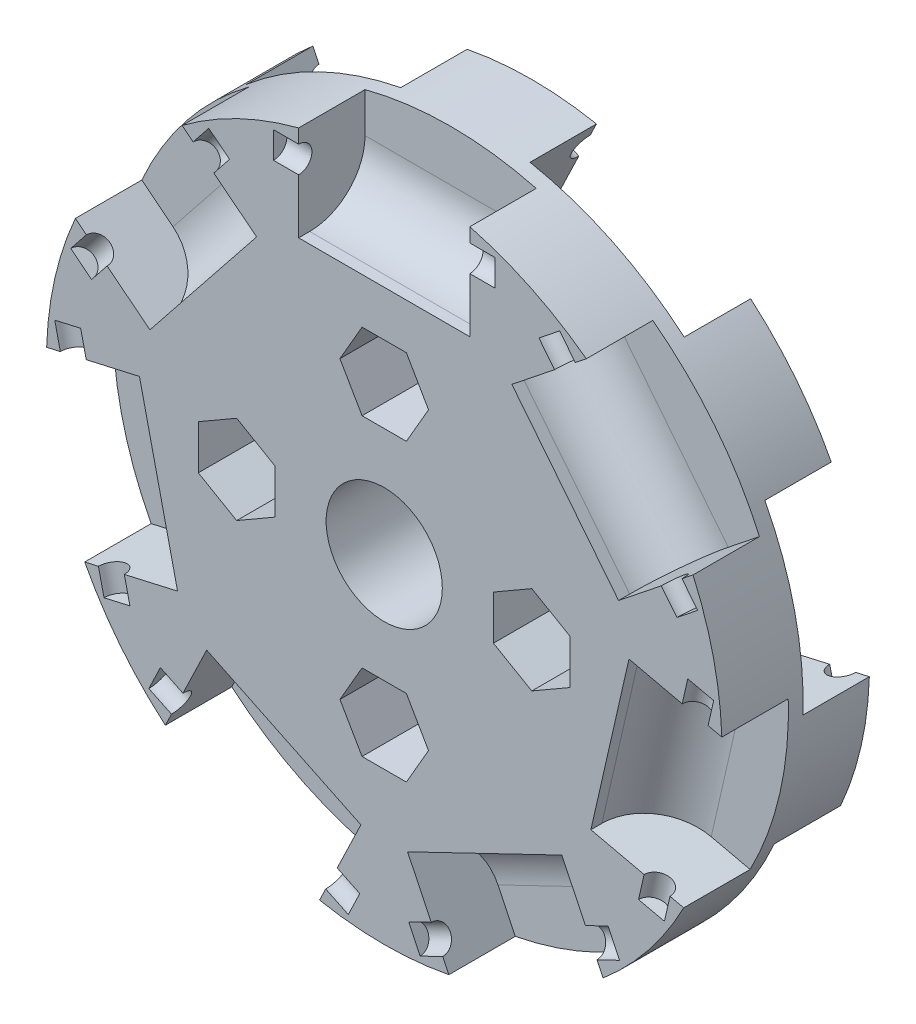
SolidWorks part; units mm, degrees
other "Markup1"
sketch "Sketch8" plane through (32.7336, 32.7336, 0) normal (0.5701, 0.1846, 0.8006) x (0.8043, 0.0736, -0.5897)
ref_plane "Front Plane" through (0, 0, 0) normal (0, 0, 1) x (1, 0, 0)
ref_plane "Top Plane" through (0, 0, 0) normal (0, 1, 0) x (1, 0, 0)
ref_plane "Right Plane" through (0, 0, 0) normal (1, 0, 0) x (0, 0, -1)
sketch "Sketch1" plane through (0, 0, 0) normal (0, 0, 1) x (1, 0, 0)
  circle A0 centre (0, 0) radius 29.0703
  dimension "D1" = 58.1406
extrude "Boss-Extrude2" add sketch "Sketch1" against normal blind 6.35
sketch "Sketch2" plane through (0, 0, 0) normal (0, 0, 1) x (1, 0, 0)
  line L1 (-12.7, 29.0703) -> (12.7, 29.0703) construction
  line L2 (-7.366, 30.3403) -> (7.366, 30.3403)
  line L3 (-7.366, 30.3403) -> (-7.366, 19.9263)
  line L4 (-7.366, 19.9263) -> (7.366, 19.9263)
  line L5 (7.366, 30.3403) -> (7.366, 19.9263)
  line L6 (-7.366, 30.3403) -> (7.366, 19.9263) construction
  line L7 (-7.366, 19.9263) -> (7.366, 30.3403) construction
  line L35 (0, 0) -> (0, 29.0703) construction
  circle A1 centre (0, 0) radius 29.0703 construction
  point P10 (0, 25.1333)
  circle M7 centre (0, 0) radius 29.0703
  dimension "D1" = 14.732
  dimension "D2" = 10.414
  dimension "D3" = 1.27
  dimension "D4" = 25.4
extrude "Cut-Extrude2" cut sketch "Sketch2" against normal blind 5.715 contours L5 L3 L4 M7
pattern_circular "CirPattern1" count 7 over 360 about axis through (0, 0, 0) along (0, 0, 1) of "Cut-Extrude2"
ref_plane "Plane1" through (0, 0, 0) normal (1, 0, 0) x (0, 0, -1)
sketch "Sketch4" plane through (0, 0, 0) normal (1, 0, 0) x (0, 0, -1)
  line L0 (5.715, 19.9263) -> (0, 19.9263) construction
  circle A0 centre (0, 25.7683) radius 1.143
  dimension "D1" = 2.286
  dimension "D2" = 5.842
extrude "Cut-Extrude4" cut sketch "Sketch4" against normal mid plane 19.05
pattern_circular "CirPattern2" count 7 over 360 about axis through (0, 0, 0) along (0, 0, 1) of "Cut-Extrude4"
sketch "Sketch6" plane through (0, 0, -6.35) normal (0, 0, -1) x (-1, 0, 0)
  line L0 (12.7, -3.8128) -> (16.002, -1.9064)
  line L1 (16.002, -1.9064) -> (16.002, 1.9064)
  line L2 (16.002, 1.9064) -> (12.7, 3.8128)
  line L3 (3.8128, 12.7) -> (1.9064, 16.002)
  line L4 (1.9064, 16.002) -> (-1.9064, 16.002)
  line L5 (-1.9064, 16.002) -> (-3.8128, 12.7)
  line L6 (-3.8128, 12.7) -> (-1.9064, 9.398)
  line L7 (-1.9064, 9.398) -> (1.9064, 9.398)
  line L8 (1.9064, 9.398) -> (3.8128, 12.7)
  line L9 (12.7, 3.8128) -> (9.398, 1.9064)
  line L10 (9.398, 1.9064) -> (9.398, -1.9064)
  line L11 (9.398, -1.9064) -> (12.7, -3.8128)
  line L12 (-3.8128, -12.7) -> (-1.9064, -16.002)
  line L13 (-1.9064, -16.002) -> (1.9064, -16.002)
  line L14 (1.9064, -16.002) -> (3.8128, -12.7)
  line L15 (3.8128, -12.7) -> (1.9064, -9.398)
  line L16 (1.9064, -9.398) -> (-1.9064, -9.398)
  line L17 (-1.9064, -9.398) -> (-3.8128, -12.7)
  line L18 (-12.7, 3.8128) -> (-16.002, 1.9064)
  line L19 (-16.002, 1.9064) -> (-16.002, -1.9064)
  line L20 (-16.002, -1.9064) -> (-12.7, -3.8128)
  line L21 (-12.7, -3.8128) -> (-9.398, -1.9064)
  line L22 (-9.398, -1.9064) -> (-9.398, 1.9064)
  line L23 (-9.398, 1.9064) -> (-12.7, 3.8128)
  circle A4 centre (0, 12.7) radius 3.302 construction
  circle A5 centre (12.7, 0) radius 3.302 construction
  circle A6 centre (0, -12.7) radius 3.302 construction
  circle A7 centre (-12.7, 0) radius 3.302 construction
  dimension "D3" = 4
  dimension "D1" = 6.604
  dimension "D2" = 12.7
extrude "Cut-Extrude7" cut sketch "Sketch6" against normal through all
sketch "Sketch9" plane through (0, 0, -6.35) normal (0, 0, -1) x (-1, 0, 0)
  line L7 (12.7, -3.8128) -> (16.002, -1.9064)
  line L8 (3.8128, 12.7) -> (1.9064, 16.002)
  line L9 (1.9064, 16.002) -> (-1.9064, 16.002)
  line L10 (-1.9064, 16.002) -> (-3.8128, 12.7)
  line L11 (-3.8128, 12.7) -> (-1.9064, 9.398)
  line L12 (-1.9064, 9.398) -> (1.9064, 9.398)
  line L13 (1.9064, 9.398) -> (3.8128, 12.7)
  line L14 (16.002, -1.9064) -> (16.002, 1.9064)
  line L15 (16.002, 1.9064) -> (12.7, 3.8128)
  line L16 (12.7, 3.8128) -> (9.398, 1.9064)
  line L17 (9.398, 1.9064) -> (9.398, -1.9064)
  line L18 (9.398, -1.9064) -> (12.7, -3.8128)
  line L19 (-3.8128, -12.7) -> (-1.9064, -16.002)
  line L20 (-1.9064, -16.002) -> (1.9064, -16.002)
  line L21 (1.9064, -16.002) -> (3.8128, -12.7)
  line L22 (3.8128, -12.7) -> (1.9064, -9.398)
  line L23 (1.9064, -9.398) -> (-1.9064, -9.398)
  line L24 (-1.9064, -9.398) -> (-3.8128, -12.7)
  line L25 (-12.7, 3.8128) -> (-16.002, 1.9064)
  line L26 (-16.002, 1.9064) -> (-16.002, -1.9064)
  line L27 (-16.002, -1.9064) -> (-12.7, -3.8128)
  line L28 (-12.7, -3.8128) -> (-9.398, -1.9064)
  line L29 (-9.398, -1.9064) -> (-9.398, 1.9064)
  line L30 (-9.398, 1.9064) -> (-12.7, 3.8128)
  circle A0 centre (0, 0) radius 29.0703
  circle A5 centre (0, 12.7) radius 3.302 construction
  circle A6 centre (12.7, 0) radius 3.302 construction
  circle A7 centre (0, -12.7) radius 3.302 construction
  circle A8 centre (-12.7, 0) radius 3.302 construction
  circle A9 centre (0, 0) radius 29.0703 construction
  point P8 (0, 0)
  point P11 (0, 0)
  point P14 (0, 0)
  point P15 (0, 0)
  dimension "D3" = 4
extrude "Boss-Extrude3" add sketch "Sketch9" along normal blind 6.35
sketch "Sketch10" plane through (0, 0, -12.7) normal (0, 0, -1) x (-1, 0, 0)
  line L0 (-25.313, 26.1915) -> (0.087, 26.1915) construction
  line L1 (-2.0091, 21.149) -> (-15.2822, 14.7571)
  line L2 (-2.0091, 21.149) -> (-6.5275, 30.5317)
  line L3 (-6.5275, 30.5317) -> (-19.8006, 24.1398)
  line L4 (-15.2822, 14.7571) -> (-19.8006, 24.1398)
  line L5 (-2.0091, 21.149) -> (-19.8006, 24.1398) construction
  line L6 (-6.5275, 30.5317) -> (-15.2822, 14.7571) construction
  line L7 (0, 0) -> (-12.613, 26.1915) construction
  line L8 (0, 0) -> (0, 40.3277) construction
  circle A2 centre (0, 0) radius 29.0703 construction
  point P8 (-10.9048, 22.6444)
  dimension "D1" = 1.27
  dimension "D2" = 14.732
  dimension "D3" = 10.414
  dimension "D4" = 25.4
  dimension "D5" = 25.714
extrude "Cut-Extrude8" cut sketch "Sketch10" against normal blind 5.715
pattern_circular "CirPattern3" count 7 over 360 about axis through (0, 0, 0) along (0, 0, 1) of "Cut-Extrude8"
ref_plane "Plane2" through (0, 0, 0) normal (-0.901, 0.4339, 0) x (0, 0, -1)
sketch "Sketch11" plane through (0, 0, 0) normal (-0.901, 0.4339, 0) x (0, 0, -1)
  line L5 (6.985, -19.9263) -> (12.7, -19.9263) construction
  line L6 (12.7, -28.1216) -> (12.7, -23.2925) construction
  circle A0 centre (12.7, -25.7683) radius 1.143
  dimension "D1" = 2.286
  dimension "D2" = 5.842
extrude "Cut-Extrude9" cut sketch "Sketch11" against normal mid plane 19.05
pattern_circular "CirPattern4" count 7 over 360 about axis through (0, 0, 0) along (0, 0, 1) of "Cut-Extrude9"
fillet "Fillet1" radius 4.7625 14 edges at (-15.579, 12.4238, -5.715) (0, 19.9263, -5.715) (8.6456, 17.953, -6.985) (-8.6458, 17.9529, -6.985) (-19.4267, 4.4339, -6.985) (-15.5789, -12.4239, -6.985) (0.0001, -19.9263, -6.985) (8.6457, -17.953, -5.715) (15.5791, -12.4238, -6.985) (19.4267, 4.4341, -6.985) (19.4267, -4.434, -5.715) (-19.4267, -4.434, -5.715) (-8.6457, -17.953, -5.715) (15.579, 12.4238, -5.715)
sketch "Sketch12" plane through (0, 0, 0) normal (0, 0, 1) x (1, 0, 0)
  circle A0 centre (0, 0) radius 5
  point P2 (0, 0)
  point P3 (0, 0)
  dimension "D1" = 10
extrude "Cut-Extrude12" cut sketch "Sketch12" against normal blind 13.716 contours A0
